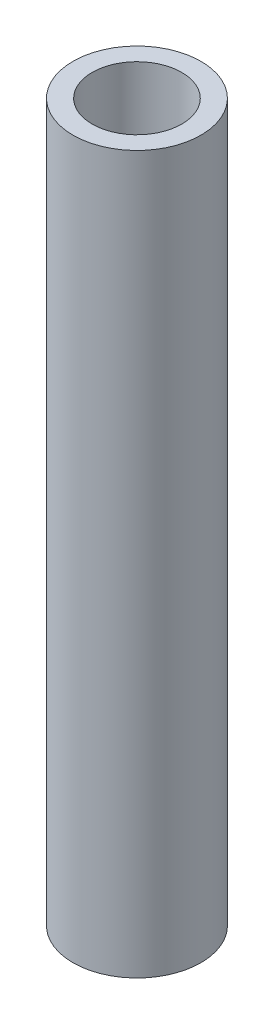
SolidWorks part; units mm, degrees
ref_plane "Front Plane" through (0, 0, 0) normal (0, 0, 1) x (1, 0, 0)
ref_plane "Top Plane" through (0, 0, 0) normal (0, 1, 0) x (1, 0, 0)
ref_plane "Right Plane" through (0, 0, 0) normal (1, 0, 0) x (0, 0, -1)
sketch "Sketch1" plane through (0, 0, 0) normal (0, 1, 0) x (1, 0, 0)
  circle A0 centre (-1.4458, 0.1843) radius 1.75
  circle A1 centre (-1.4458, 0.1843) radius 2.5
  dimension "D1" = 3.5
  dimension "D2" = 5
extrude "Boss-Extrude1" add sketch "Sketch1" along normal blind 28
